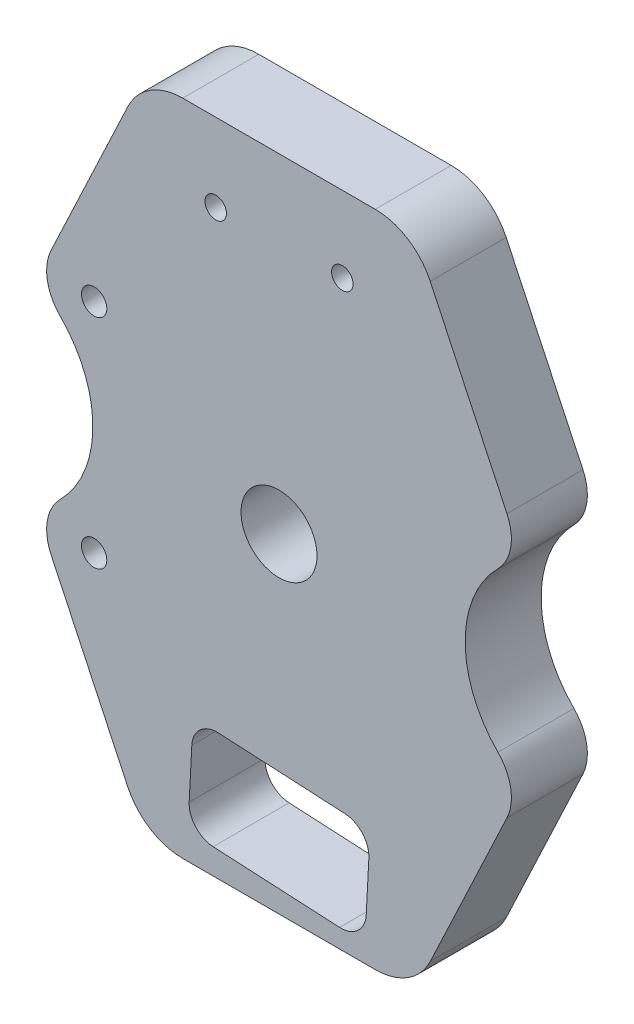
SolidWorks part; units mm, degrees
ref_plane "Płaszczyzna przednia" through (0, 0, 0) normal (0, 0, 1) x (1, 0, 0)
ref_plane "Płaszczyzna górna" through (0, 0, 0) normal (0, 1, 0) x (1, 0, 0)
ref_plane "Płaszczyzna prawa" through (0, 0, 0) normal (1, 0, 0) x (0, 0, -1)
sketch "Szkic1" plane through (0, 0, 0) normal (0, 0, 1) x (1, 0, 0)
  line L3 (0, 260) -> (0, 0) construction
  line L5 (0, 130) -> (-92.5, 130) construction
  line L6 (25, 230) -> (-113.1637, 230) construction
  line L7 (-38, 260) -> (38, 260)
  line L8 (59.7094, 246.2323) -> (90.0082, 181.9488)
  line L9 (59.7662, 13.7409) -> (90.0082, 77.9041)
  line L10 (0, 0) -> (38, 0)
  line L11 (-59.7662, 13.7409) -> (-90.0082, 77.9041)
  line L12 (-59.7094, 246.2323) -> (-90.0082, 181.9488)
  line L13 (-38, 0) -> (0, 0)
  line L14 (25, 230) -> (-114.4641, 227.5656) construction
  line L15 (-25, 30) -> (78.9798, 30) construction
  line L16 (-25, 30) -> (79.6859, 24.5136) construction
  circle A0 centre (0, 130) radius 15
  circle A2 centre (-73, 87) radius 5
  circle A3 centre (-73, 173) radius 5
  arc A4 (86.4422, 161.3009) -> (86.4422, 98.552) centre (118, 129.9265) ccw
  circle A5 centre (25, 230) radius 50 construction
  arc A6 (86.4422, 98.552) -> (90.0082, 77.9041) centre (73.5, 85.6849) cw
  arc A7 (86.4422, 161.3009) -> (90.0082, 181.9488) centre (73.5, 174.168) ccw
  circle A8 centre (25, 230) radius 4.25
  arc A9 (59.7094, 246.2323) -> (38, 260) centre (38, 236) ccw
  arc A11 (59.7662, 13.7409) -> (38, 0) centre (38.0693, 23.9999) cw
  arc A12 (-59.7662, 13.7409) -> (-38, 0) centre (-38.0693, 23.9999) ccw
  arc A13 (-86.4422, 98.552) -> (-90.0082, 77.9041) centre (-73.5, 85.6849) ccw
  arc A14 (-86.4422, 161.3009) -> (-86.4422, 98.552) centre (-118, 129.9265) cw
  arc A15 (-86.4422, 161.3009) -> (-90.0082, 181.9488) centre (-73.5, 174.168) cw
  arc A16 (-59.7094, 246.2323) -> (-38, 260) centre (-38, 236) cw
  circle A18 centre (-24.9924, 229.1274) radius 4.25
  circle A20 centre (-25, 30) radius 4.25
  circle A21 centre (-25, 30) radius 50 construction
  circle A22 centre (24.9315, 27.3832) radius 4.25
  point P23 (96.4639, 168.868)
  dimension "D1" = 18.25
  dimension "D2" = 30
  dimension "D3" = 1
  dimension "D6" = 44.5
  dimension "D7" = 10
  dimension "D10" = 38
  dimension "D4" = 24
  dimension "D11" = 48
  dimension "D12" = 130
  dimension "D13" = 73.5
  dimension "D16" = 73
  dimension "D17" = 8.5
  dimension "D18" = 118
  dimension "D5" = 8.5
  dimension "D19" = 100
  dimension "D20" = 3
  dimension "D21" = 8.5
  dimension "D22" = 8.5
  dimension "D23" = 30
  dimension "D24" = 27.3832
  dimension "D25" = 25
  dimension "D26" = 100
  dimension "D8" = 25
  dimension "D9" = 30
  dimension "D14" = 73.5
  dimension "D15" = 43
extrude "Dodanie-wyciągnięcie1" add sketch "Szkic1" along normal blind 30
sketch "Szkic2" plane through (0, 0, 30) normal (0, 0, 1) x (1, 0, 0)
  line L1 (0, 260) -> (0, -13.2421) construction
  line L2 (38, 260) -> (-38, 260) construction
  line L12 (-88.8511, 130) -> (90.6766, 130) construction
  point P4 (0, 230)
  point P19 (0, 245)
sketch "Szkic3" plane through (0, 0, 0) normal (0, 0, -1) x (-1, 0, 0)
  circle A0 centre (25, 30) radius 4
  circle A1 centre (-24.9315, 27.3832) radius 4
  circle A2 centre (24.9924, 229.1274) radius 4
  circle A3 centre (-25, 230) radius 4
ref_plane "Płaszczyzna1" through (-86.4422, 98.552, 0) normal (0, 0, -1) x (-1, 0, 0)
sketch "Szkic4" plane through (-86.4422, 98.552, 0) normal (0, 0, -1) x (-1, 0, 0)
  line L0 (-52.5369, -48.0578) -> (-50.4435, -88.003)
  line L1 (-122.441, -51.7213) -> (-120.3475, -91.6665)
  line L2 (-86.4422, 161.448) -> (-86.4422, -111.7941) construction
  line L3 (-122.441, -51.7213) -> (-52.5369, -48.0578)
  line L4 (-121.3943, -71.6939) -> (-51.4902, -68.0304) construction
  line L5 (-50.4435, -88.003) -> (-120.3475, -91.6665)
  point P2 (-51.4902, -68.0304)
  point P9 (-121.3943, -71.6939)
  point P13 (-86.4422, -69.8622)
  dimension "D1" = 70
  dimension "D2" = 40
extrude "Wytnij-wyciągnięcie1" cut sketch "Szkic4" against normal blind 30
fillet "Zaokrąglenie1" radius 10 4 edges at (33.9053, 6.8855, 15) (-35.9988, 10.549, 15) (-33.9053, 50.4942, 15) (35.9988, 46.8306, 15)
sketch "Szkic5" plane through (0, 0, 0) normal (0, 0, -1) x (-1, 0, 0)
  line L0 (1.5036, 0) -> (-1.415, 55.6904)
  line L1 (23.919, 49.9708) -> (-26.0125, 47.354) construction
  line L2 (-23.919, 7.4088) -> (26.0125, 10.0256) construction
  line L3 (38, 0) -> (-38, 0) construction
  point P7 (-1.0467, 48.6624)
